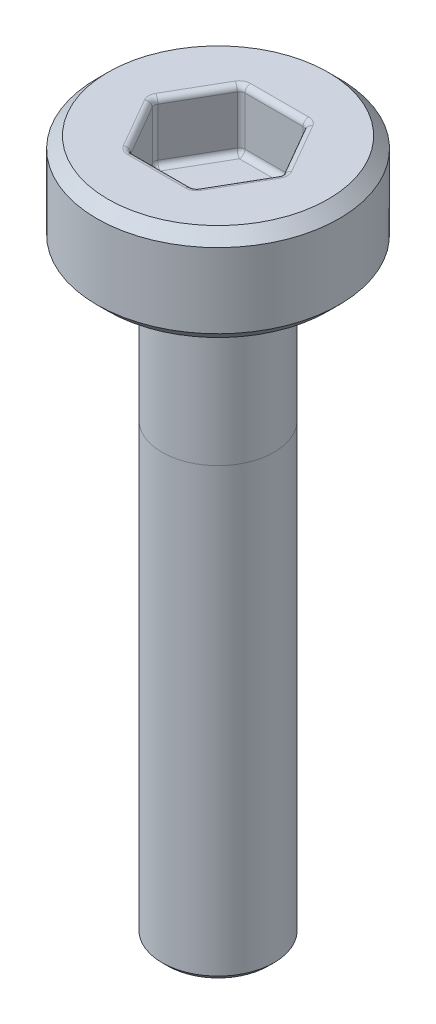
SolidWorks part; units mm, degrees
ref_plane "Front Plane" through (0, 0, 0) normal (0, 0, 1) x (1, 0, 0)
ref_plane "Top Plane" through (0, 0, 0) normal (0, 1, 0) x (1, 0, 0)
ref_plane "Right Plane" through (0, 0, 0) normal (1, 0, 0) x (0, 0, -1)
sketch "Sketch1" plane through (0, 0, 0) normal (0, 1, 0) x (1, 0, 0)
  circle A0 centre (0, 0) radius 0.75
  dimension "D1" = 1.5
extrude "Boss-Extrude1" add sketch "Sketch1" along normal blind 8
sketch "Sketch2" plane through (0, 8, 0) normal (0, 1, 0) x (1, 0, 0)
  circle A0 centre (0, 0) radius 1.625
  dimension "D1" = 3.25
extrude "Boss-Extrude2" add sketch "Sketch2" along normal blind 1.3
fillet "Fillet1" radius 0.15 1 edges at (0, 8, 0.75)
chamfer "Chamfer1" distance 0.15 angle 45 2 edges at (0, 9.3, 1.625) (0, 8, 1.625)
sketch "Sketch3" plane through (0, 9.3, 0) normal (0, 1, 0) x (1, 0, 0)
  line L1 (-0.433, 0.75) -> (-0.866, 0)
  line L2 (-0.866, 0) -> (-0.433, -0.75)
  line L3 (-0.433, -0.75) -> (0.433, -0.75)
  line L4 (0.433, -0.75) -> (0.866, 0)
  line L5 (0.866, 0) -> (0.433, 0.75)
  line L6 (0.433, 0.75) -> (-0.433, 0.75)
  circle A0 centre (0, 0) radius 0.75 construction
  dimension "D1" = 1.5
extrude "Cut-Extrude1" cut sketch "Sketch3" against normal blind 0.8
chamfer "Chamfer2" distance 0.075 angle 45 1 edges at (0, 0, 0.75)
fillet "Fillet2" radius 0.075 18 edges at (0, 9.3, -0.75) (-0.6495, 9.3, -0.375) (-0.6495, 9.3, 0.375) (0, 9.3, 0.75) (0.6495, 9.3, 0.375) (0.6495, 9.3, -0.375) (-0.6495, 8.5, -0.375) (-0.6495, 8.5, 0.375) (0, 8.5, 0.75) (0.6495, 8.5, 0.375) (0.6495, 8.5, -0.375) (-0.433, 8.9, -0.75) (-0.866, 8.9, 0) (-0.433, 8.9, 0.75) (0.433, 8.9, 0.75) (0.866, 8.9, 0) (0.433, 8.9, -0.75) (0, 8.5, -0.75)
sketch "Sketch4" plane through (0, 0, 0) normal (0, 0, 1) x (1, 0, 0)
  line L0 (-5.6741, 6) -> (6.8738, 6)
  dimension "D1" = 6
split line "Split Line1"
